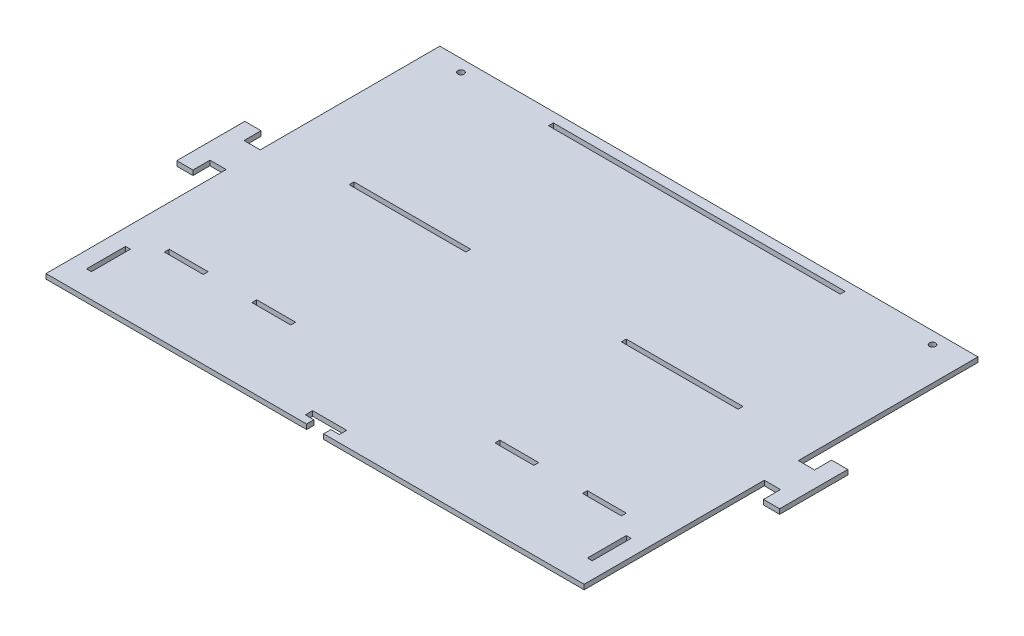
SolidWorks part; units mm, degrees
ref_plane "Alzado" through (0, 0, 0) normal (0, 0, 1) x (1, 0, 0)
ref_plane "Planta" through (0, 0, 0) normal (0, 1, 0) x (1, 0, 0)
ref_plane "Vista lateral" through (0, 0, 0) normal (1, 0, 0) x (0, 0, -1)
sketch "Croquis1" plane through (0, 0, 0) normal (0, 1, 0) x (1, 0, 0)
  line L4 (-447.0447, -95.6027) -> (-447.0447, -240.6027)
  line L5 (-2097.0447, -803.1027) -> (-437.0447, -803.1027)
  line L6 (-437.0447, 6.8973) -> (-437.0447, -803.1027)
  line L7 (-2097.0447, 6.8973) -> (-437.0447, 6.8973)
  line L13 (-2097.0447, 6.8973) -> (-2097.0447, -803.1027)
  line L18 (-2087.0447, -793.1027) -> (-447.0447, -793.1027) construction
  line L19 (-932.0447, -3.1027) -> (-632.0447, -3.1027)
  line L25 (-2097.0447, 6.8973) -> (-2097.0447, -803.1027) construction
  line L29 (-1117.0447, -3.1027) -> (-1417.0447, -3.1027)
  line L30 (-1117.0447, -8.1027) -> (-1117.0447, -3.1027)
  line L32 (-1417.0447, -3.1027) -> (-1417.0447, -8.1027)
  line L33 (-1602.0447, -8.1027) -> (-1902.0447, -8.1027)
  line L34 (-1902.0447, -3.1027) -> (-1602.0447, -3.1027)
  line L35 (-1902.0447, -3.1027) -> (-1902.0447, -8.1027)
  line L36 (-1602.0447, -3.1027) -> (-1602.0447, -8.1027)
  line L37 (-2097.0447, 6.8973) -> (-437.0447, 6.8973)
  line L38 (-632.0447, -3.1027) -> (-632.0447, -8.1027)
  line L39 (-2087.0447, -3.1027) -> (-447.0447, -3.1027) construction
  line L40 (-932.0447, -3.1027) -> (-932.0447, -8.1027)
  line L41 (-452.0447, -95.6027) -> (-452.0447, -90.6027)
  line L42 (-447.0447, -3.1027) -> (-447.0447, -793.1027) construction
  line L45 (-452.0447, -95.6027) -> (-452.0447, -240.6027)
  line L49 (-452.0447, -328.1027) -> (-452.0447, -473.1027)
  line L51 (-447.0447, -328.1027) -> (-447.0447, -473.1027)
  line L53 (-452.0447, -560.6027) -> (-452.0447, -705.6027)
  line L55 (-447.0447, -560.6027) -> (-447.0447, -705.6027)
  line L67 (-2087.0447, -3.1027) -> (-2087.0447, -793.1027) construction
  line L68 (-447.0447, -95.6027) -> (-447.0447, -90.6027)
  line L69 (-447.0447, -90.6027) -> (-452.0447, -90.6027)
  line L70 (-447.0447, -328.1027) -> (-447.0447, -323.1027)
  line L71 (-447.0447, -240.6027) -> (-452.0447, -240.6027) construction
  line L72 (-447.0447, -240.6027) -> (-452.0447, -240.6027)
  line L73 (-452.0447, -328.1027) -> (-452.0447, -323.1027)
  line L74 (-452.0447, -323.1027) -> (-447.0447, -323.1027)
  line L75 (-447.0447, -473.1027) -> (-452.0447, -473.1027)
  line L76 (-452.0447, -560.6027) -> (-452.0447, -555.6027)
  line L77 (-447.0447, -560.6027) -> (-447.0447, -555.6027)
  line L78 (-447.0447, -555.6027) -> (-452.0447, -555.6027)
  line L79 (-632.0447, -8.1027) -> (-932.0447, -8.1027)
  line L80 (-447.0447, -705.6027) -> (-452.0447, -705.6027)
  line L81 (-2087.0447, -240.6027) -> (-2082.0447, -240.6027) construction
  line L82 (-2087.0447, -705.6027) -> (-2082.0447, -705.6027)
  line L83 (-2087.0447, -555.6027) -> (-2082.0447, -555.6027)
  line L84 (-2087.0447, -560.6027) -> (-2087.0447, -555.6027)
  line L85 (-2082.0447, -560.6027) -> (-2082.0447, -555.6027)
  line L86 (-2087.0447, -473.1027) -> (-2082.0447, -473.1027)
  line L87 (-2082.0447, -323.1027) -> (-2087.0447, -323.1027)
  line L88 (-2082.0447, -328.1027) -> (-2082.0447, -323.1027)
  line L89 (-2087.0447, -240.6027) -> (-2082.0447, -240.6027)
  line L90 (-2087.0447, -328.1027) -> (-2087.0447, -323.1027)
  line L91 (-2087.0447, -90.6027) -> (-2082.0447, -90.6027)
  line L92 (-2087.0447, -95.6027) -> (-2087.0447, -90.6027)
  line L93 (-2087.0447, -560.6027) -> (-2087.0447, -705.6027)
  line L94 (-2082.0447, -560.6027) -> (-2082.0447, -705.6027)
  line L95 (-2087.0447, -328.1027) -> (-2087.0447, -473.1027)
  line L96 (-2082.0447, -328.1027) -> (-2082.0447, -473.1027)
  line L97 (-2082.0447, -95.6027) -> (-2082.0447, -240.6027)
  line L98 (-2082.0447, -95.6027) -> (-2082.0447, -90.6027)
  line L99 (-2087.0447, -95.6027) -> (-2087.0447, -240.6027)
  line L100 (-1117.0447, -8.1027) -> (-1417.0447, -8.1027)
  line L101 (-1117.0447, -788.1027) -> (-1417.0447, -788.1027)
  line L102 (-632.0447, -788.1027) -> (-932.0447, -788.1027)
  line L103 (-932.0447, -793.1027) -> (-932.0447, -788.1027)
  line L104 (-632.0447, -793.1027) -> (-632.0447, -788.1027)
  line L105 (-1602.0447, -793.1027) -> (-1602.0447, -788.1027)
  line L106 (-1902.0447, -793.1027) -> (-1902.0447, -788.1027)
  line L107 (-1902.0447, -793.1027) -> (-1602.0447, -793.1027)
  line L108 (-1602.0447, -788.1027) -> (-1902.0447, -788.1027)
  line L109 (-1417.0447, -793.1027) -> (-1417.0447, -788.1027)
  line L110 (-1117.0447, -788.1027) -> (-1117.0447, -793.1027)
  line L111 (-1117.0447, -793.1027) -> (-1417.0447, -793.1027)
  line L112 (-932.0447, -793.1027) -> (-632.0447, -793.1027)
  dimension "D5" = 5
  dimension "D10" = 145
  dimension "D3" = 1660
  dimension "D12" = 5
  dimension "D13" = 145
  dimension "D14" = 5
  dimension "D15" = 5
extrude "Saliente-Extruir3" add sketch "Croquis1" along normal blind 5 contours L7 L13 L5 L6 L112 L103 L102 L104 L108 L105 L107 L106 L99 L92 L91 L98 L97 L89 L34 L36 L33 L35 L4 L72 L45 L41 L69 L68 L51 L75 L49 L73 L74 L70 L38 L79 L40 L19 L55 L80 L53 L76 L78
sketch "Croquis2" plane through (0, 5, 0) normal (0, 1, 0) x (1, 0, 0)
  line L0 (-1007.0447, -463.1027) -> (-1007.0447, -423.1027)
  line L1 (-669.5447, -638.1027) -> (-699.5447, -638.1027)
  line L2 (-1067.0447, -638.1027) -> (-1187.0447, -638.1027)
  line L5 (-1467.0447, -633.1027) -> (-1347.0447, -633.1027)
  line L8 (-1602.0447, -788.1027) -> (-1902.0447, -788.1027) construction
  line L11 (-1672.0447, -788.1027) -> (-1667.0447, -788.1027)
  line L19 (-644.5447, -633.1027) -> (-644.5447, -638.1027)
  line L24 (-1464.5447, -483.1027) -> (-1344.5447, -483.1027)
  line L25 (-669.5447, -638.1027) -> (-669.5447, -633.1027)
  line L26 (-1672.0447, -8.1027) -> (-1667.0447, -8.1027)
  line L61 (-769.5447, -478.1027) -> (-802.0447, -478.1027)
  line L63 (-849.5447, -483.1027) -> (-817.0447, -483.1027)
  line L65 (-602.0447, -490.6027) -> (-602.0447, -535.6027)
  line L68 (-699.5447, -633.1027) -> (-669.5447, -633.1027)
  line L70 (-862.0447, -653.1027) -> (-862.0447, -698.1027)
  line L72 (-867.0447, -653.1027) -> (-867.0447, -698.1027)
  line L74 (-1032.0447, -313.1027) -> (-1072.0447, -313.1027)
  line L76 (-1162.0447, -318.1027) -> (-1122.0447, -318.1027)
  line L77 (-1012.0447, -333.1027) -> (-1012.0447, -373.1027)
  line L78 (-1064.5447, -478.1027) -> (-1184.5447, -478.1027)
  line L80 (-1122.0447, -313.1027) -> (-1122.0447, -318.1027)
  line L87 (-699.5447, -633.1027) -> (-699.5447, -638.1027)
  line L88 (-614.5447, -638.1027) -> (-644.5447, -638.1027)
  line L89 (-614.5447, -638.1027) -> (-614.5447, -633.1027)
  line L90 (-607.0447, -615.6027) -> (-602.0447, -615.6027)
  line L91 (-607.0447, -570.6027) -> (-602.0447, -570.6027)
  line L92 (-602.0447, -570.6027) -> (-602.0447, -615.6027)
  line L93 (-607.0447, -490.6027) -> (-607.0447, -535.6027)
  line L94 (-1187.0447, -158.1027) -> (-1187.0447, -163.1027)
  line L95 (-607.0447, -535.6027) -> (-602.0447, -535.6027)
  line L96 (-607.0447, -615.6027) -> (-607.0447, -570.6027)
  line L97 (-802.0447, -478.1027) -> (-802.0447, -483.1027)
  line L99 (-604.5447, -535.6027) -> (-602.0447, -535.6027) construction
  line L100 (-817.0447, -483.1027) -> (-817.0447, -478.1027)
  line L101 (-644.5447, -633.1027) -> (-614.5447, -633.1027)
  line L102 (-1467.0447, -158.1027) -> (-1467.0447, -163.1027)
  line L103 (-867.0447, -653.1027) -> (-862.0447, -653.1027)
  line L104 (-867.0447, -698.1027) -> (-862.0447, -698.1027)
  line L105 (-862.0447, -728.1027) -> (-867.0447, -728.1027)
  line L106 (-862.0447, -728.1027) -> (-862.0447, -773.1027)
  line L107 (-867.0447, -728.1027) -> (-867.0447, -773.1027)
  line L108 (-867.0447, -773.1027) -> (-862.0447, -773.1027)
  line L109 (-1347.0447, -638.1027) -> (-1467.0447, -638.1027)
  line L110 (-849.5447, -478.1027) -> (-849.5447, -483.1027)
  line L111 (-769.5447, -483.1027) -> (-769.5447, -478.1027)
  line L112 (-802.0447, -483.1027) -> (-769.5447, -483.1027)
  line L113 (-817.0447, -478.1027) -> (-849.5447, -478.1027)
  line L114 (-1267.0447, -8.1027) -> (-1267.0447, -98.1027)
  line L115 (-1064.5447, -478.1027) -> (-1064.5447, -483.1027)
  line L116 (-1184.5447, -478.1027) -> (-1184.5447, -483.1027)
  line L117 (-1464.5447, -478.1027) -> (-1464.5447, -483.1027)
  line L118 (-1344.5447, -478.1027) -> (-1344.5447, -483.1027)
  line L121 (-1184.5447, -483.1027) -> (-1064.5447, -483.1027)
  line L122 (-1344.5447, -478.1027) -> (-1464.5447, -478.1027)
  line L123 (-1117.0447, -8.1027) -> (-1417.0447, -8.1027) construction
  line L124 (-1412.0447, -313.1027) -> (-1412.0447, -318.1027) construction
  line L126 (-1067.0447, -633.1027) -> (-1067.0447, -638.1027)
  line L127 (-1187.0447, -638.1027) -> (-1187.0447, -633.1027)
  line L128 (-1347.0447, -638.1027) -> (-1347.0447, -633.1027)
  line L129 (-1467.0447, -633.1027) -> (-1467.0447, -638.1027)
  line L130 (-1187.0447, -633.1027) -> (-1067.0447, -633.1027)
  line L131 (-1412.0447, -313.1027) -> (-1372.0447, -313.1027)
  line L132 (-1927.0447, -305.6027) -> (-1932.0447, -305.6027)
  line L133 (-1462.0447, -318.1027) -> (-1502.0447, -318.1027)
  line L134 (-1012.0447, -423.1027) -> (-1012.0447, -463.1027)
  line L136 (-1012.0447, -463.1027) -> (-1007.0447, -463.1027)
  line L137 (-1012.0447, -423.1027) -> (-1007.0447, -423.1027)
  line L138 (-1012.0447, -373.1027) -> (-1007.0447, -373.1027)
  line L139 (-1007.0447, -333.1027) -> (-1012.0447, -333.1027)
  line L140 (-1007.0447, -373.1027) -> (-1007.0447, -333.1027)
  line L141 (-1032.0447, -313.1027) -> (-1032.0447, -318.1027)
  line L142 (-1072.0447, -313.1027) -> (-1072.0447, -318.1027)
  line L143 (-1372.0447, -313.1027) -> (-1372.0447, -318.1027)
  line L144 (-1162.0447, -313.1027) -> (-1162.0447, -318.1027)
  line L145 (-1122.0447, -313.1027) -> (-1122.0447, -318.1027) construction
  line L146 (-1072.0447, -318.1027) -> (-1032.0447, -318.1027)
  line L147 (-1122.0447, -313.1027) -> (-1162.0447, -313.1027)
  line L148 (-1929.5447, -535.6027) -> (-1932.0447, -535.6027) construction
  line L149 (-1717.0447, -478.1027) -> (-1684.5447, -478.1027)
  line L150 (-1732.0447, -483.1027) -> (-1764.5447, -483.1027)
  line L151 (-1764.5447, -483.1027) -> (-1764.5447, -478.1027)
  line L152 (-1684.5447, -478.1027) -> (-1684.5447, -483.1027)
  line L153 (-1717.0447, -483.1027) -> (-1717.0447, -478.1027)
  line L154 (-1732.0447, -478.1027) -> (-1732.0447, -483.1027)
  line L155 (-1927.0447, -535.6027) -> (-1932.0447, -535.6027)
  line L156 (-1462.0447, -313.1027) -> (-1462.0447, -318.1027)
  line L157 (-1927.0447, -490.6027) -> (-1927.0447, -535.6027)
  line L159 (-1932.0447, -490.6027) -> (-1932.0447, -535.6027)
  line L160 (-1684.5447, -483.1027) -> (-1717.0447, -483.1027)
  line L161 (-1764.5447, -478.1027) -> (-1732.0447, -478.1027)
  line L162 (-1667.0447, -773.1027) -> (-1672.0447, -773.1027)
  line L163 (-1467.0447, -158.1027) -> (-1347.0447, -158.1027)
  line L164 (-1067.0447, -163.1027) -> (-1187.0447, -163.1027)
  line L165 (-1502.0447, -313.1027) -> (-1502.0447, -318.1027)
  line L166 (-1527.0447, -373.1027) -> (-1527.0447, -333.1027)
  line L167 (-1527.0447, -333.1027) -> (-1522.0447, -333.1027)
  line L168 (-1522.0447, -373.1027) -> (-1527.0447, -373.1027)
  line L169 (-1522.0447, -423.1027) -> (-1527.0447, -423.1027)
  line L170 (-1522.0447, -423.1027) -> (-1522.0447, -463.1027)
  line L171 (-1667.0447, -728.1027) -> (-1667.0447, -773.1027)
  line L172 (-1672.0447, -728.1027) -> (-1672.0447, -773.1027)
  line L173 (-1672.0447, -728.1027) -> (-1667.0447, -728.1027)
  line L174 (-1667.0447, -698.1027) -> (-1672.0447, -698.1027)
  line L175 (-1667.0447, -653.1027) -> (-1672.0447, -653.1027)
  line L176 (-1889.5447, -633.1027) -> (-1919.5447, -633.1027)
  line L177 (-1927.0447, -615.6027) -> (-1927.0447, -570.6027)
  line L178 (-1932.0447, -570.6027) -> (-1932.0447, -615.6027)
  line L179 (-1927.0447, -570.6027) -> (-1932.0447, -570.6027)
  line L180 (-1927.0447, -615.6027) -> (-1932.0447, -615.6027)
  line L181 (-1919.5447, -638.1027) -> (-1919.5447, -633.1027)
  line L182 (-1919.5447, -638.1027) -> (-1889.5447, -638.1027)
  line L183 (-1834.5447, -633.1027) -> (-1834.5447, -638.1027)
  line L184 (-1667.0447, -653.1027) -> (-1667.0447, -698.1027)
  line L185 (-1672.0447, -653.1027) -> (-1672.0447, -698.1027)
  line L186 (-1834.5447, -633.1027) -> (-1864.5447, -633.1027)
  line L187 (-1864.5447, -638.1027) -> (-1864.5447, -633.1027)
  line L188 (-1889.5447, -633.1027) -> (-1889.5447, -638.1027)
  line L189 (-1412.0447, -313.1027) -> (-1412.0447, -318.1027)
  line L190 (-1522.0447, -333.1027) -> (-1522.0447, -373.1027)
  line L191 (-1864.5447, -638.1027) -> (-1834.5447, -638.1027)
  line L192 (-1187.0447, -158.1027) -> (-1067.0447, -158.1027)
  line L193 (-1372.0447, -318.1027) -> (-1412.0447, -318.1027)
  line L194 (-1347.0447, -158.1027) -> (-1347.0447, -163.1027)
  line L195 (-1502.0447, -313.1027) -> (-1462.0447, -313.1027)
  line L196 (-1067.0447, -163.1027) -> (-1067.0447, -158.1027)
  line L197 (-1347.0447, -163.1027) -> (-1467.0447, -163.1027)
  line L198 (-1527.0447, -463.1027) -> (-1527.0447, -423.1027)
  line L199 (-1522.0447, -463.1027) -> (-1527.0447, -463.1027)
  line L200 (-1927.0447, -490.6027) -> (-1932.0447, -490.6027)
  line L201 (-602.0447, -490.6027) -> (-607.0447, -490.6027)
  line L202 (-602.0447, -305.6027) -> (-607.0447, -305.6027)
  line L206 (-604.5447, -260.6027) -> (-602.0447, -260.6027) construction
  line L207 (-817.0447, -318.1027) -> (-849.5447, -318.1027)
  line L208 (-802.0447, -313.1027) -> (-769.5447, -313.1027)
  line L209 (-769.5447, -313.1027) -> (-769.5447, -318.1027)
  line L210 (-849.5447, -318.1027) -> (-849.5447, -313.1027)
  line L211 (-867.0447, -23.1027) -> (-862.0447, -23.1027)
  line L212 (-867.0447, -68.1027) -> (-867.0447, -23.1027)
  line L213 (-862.0447, -68.1027) -> (-862.0447, -23.1027)
  line L214 (-862.0447, -68.1027) -> (-867.0447, -68.1027)
  line L215 (-867.0447, -98.1027) -> (-862.0447, -98.1027)
  line L216 (-867.0447, -143.1027) -> (-862.0447, -143.1027)
  line L217 (-644.5447, -163.1027) -> (-614.5447, -163.1027)
  line L218 (-817.0447, -313.1027) -> (-817.0447, -318.1027)
  line L219 (-802.0447, -318.1027) -> (-802.0447, -313.1027)
  line L220 (-607.0447, -180.6027) -> (-607.0447, -225.6027)
  line L221 (-607.0447, -260.6027) -> (-602.0447, -260.6027)
  line L223 (-607.0447, -305.6027) -> (-607.0447, -260.6027)
  line L224 (-602.0447, -225.6027) -> (-602.0447, -180.6027)
  line L225 (-607.0447, -225.6027) -> (-602.0447, -225.6027)
  line L226 (-607.0447, -180.6027) -> (-602.0447, -180.6027)
  line L227 (-614.5447, -158.1027) -> (-614.5447, -163.1027)
  line L228 (-614.5447, -158.1027) -> (-644.5447, -158.1027)
  line L229 (-699.5447, -163.1027) -> (-699.5447, -158.1027)
  line L230 (-867.0447, -143.1027) -> (-867.0447, -98.1027)
  line L231 (-862.0447, -143.1027) -> (-862.0447, -98.1027)
  line L232 (-699.5447, -163.1027) -> (-669.5447, -163.1027)
  line L234 (-602.0447, -305.6027) -> (-602.0447, -260.6027)
  line L235 (-849.5447, -313.1027) -> (-817.0447, -313.1027)
  line L236 (-769.5447, -318.1027) -> (-802.0447, -318.1027)
  line L237 (-669.5447, -158.1027) -> (-669.5447, -163.1027)
  line L238 (-644.5447, -163.1027) -> (-644.5447, -158.1027)
  line L239 (-669.5447, -158.1027) -> (-699.5447, -158.1027)
  line L240 (-1929.5447, -260.6027) -> (-1932.0447, -260.6027) construction
  line L241 (-1864.5447, -158.1027) -> (-1834.5447, -158.1027)
  line L242 (-1889.5447, -163.1027) -> (-1889.5447, -158.1027)
  line L243 (-1864.5447, -158.1027) -> (-1864.5447, -163.1027)
  line L244 (-1834.5447, -163.1027) -> (-1864.5447, -163.1027)
  line L245 (-1672.0447, -143.1027) -> (-1672.0447, -98.1027)
  line L246 (-1667.0447, -143.1027) -> (-1667.0447, -98.1027)
  line L247 (-1834.5447, -163.1027) -> (-1834.5447, -158.1027)
  line L248 (-1919.5447, -158.1027) -> (-1889.5447, -158.1027)
  line L249 (-1919.5447, -158.1027) -> (-1919.5447, -163.1027)
  line L250 (-1927.0447, -180.6027) -> (-1932.0447, -180.6027)
  line L251 (-1927.0447, -225.6027) -> (-1932.0447, -225.6027)
  line L252 (-1932.0447, -225.6027) -> (-1932.0447, -180.6027)
  line L253 (-1927.0447, -180.6027) -> (-1927.0447, -225.6027)
  line L254 (-1889.5447, -163.1027) -> (-1919.5447, -163.1027)
  line L255 (-1667.0447, -143.1027) -> (-1672.0447, -143.1027)
  line L256 (-1667.0447, -98.1027) -> (-1672.0447, -98.1027)
  line L257 (-1672.0447, -68.1027) -> (-1667.0447, -68.1027)
  line L258 (-1672.0447, -68.1027) -> (-1672.0447, -23.1027)
  line L259 (-1667.0447, -68.1027) -> (-1667.0447, -23.1027)
  line L260 (-1667.0447, -23.1027) -> (-1672.0447, -23.1027)
  line L261 (-1764.5447, -318.1027) -> (-1732.0447, -318.1027)
  line L262 (-1684.5447, -313.1027) -> (-1717.0447, -313.1027)
  line L263 (-1932.0447, -305.6027) -> (-1932.0447, -260.6027)
  line L265 (-1927.0447, -305.6027) -> (-1927.0447, -260.6027)
  line L267 (-1927.0447, -260.6027) -> (-1932.0447, -260.6027)
  line L268 (-1732.0447, -318.1027) -> (-1732.0447, -313.1027)
  line L269 (-1717.0447, -313.1027) -> (-1717.0447, -318.1027)
  line L270 (-1684.5447, -318.1027) -> (-1684.5447, -313.1027)
  line L271 (-1764.5447, -313.1027) -> (-1764.5447, -318.1027)
  line L272 (-1732.0447, -313.1027) -> (-1764.5447, -313.1027)
  line L273 (-1717.0447, -318.1027) -> (-1684.5447, -318.1027)
  dimension "D1" = 120
extrude "Cortar-Extruir2" cut sketch "Croquis2" against normal blind 10 contours L226 L220 L225 L224 | L238 L217 L227 L228 | L214 L213 L211 L212 | L216 L231 L215 L230 | L236 L209 L208 L219 | L235 L210 L207 L218 | L93 L95 L65 L202 | L96 L90 L92 L91 | L97 L112 L111 L61 | L100 L113 L110 L63 | L107 L108 L106 L105 | L175 L185 L174 L184 | L173 L172 L162 L171 | L187 L191 L183 L186 | L259 L260 L258 L257 | L246 L256 L245 L255 | L232 L237 L239 L229 | L101 L89 L88 L19 | L68 L25 L1 L87 | L70 L104 L72 L103 | L134 L136 L0 L137 | L78 L116 L121 L115 | L77 L138 L140 L139 | L74 L142 L146 L141 | L76 L80 L147 L144 | L164 L94 L192 L196 | L130 L126 L2 L127 | L24 L118 L122 L117 | L163 L194 L197 L102 | L5 L128 L109 L129 | L176 L181 L182 L188 | L177 L179 L178 L180 | L159 L155 L157 L200 | L263 L267 L265 L132 | L252 L250 L253 L251 | L248 L242 L254 L249 | L241 L247 L244 L243 | L262 L269 L273 L270 | L149 L152 L160 L153 | L150 L151 L161 L154 | L261 L268 L272 L271 | L166 L167 L190 L168 | L169 L198 L199 L170 | L133 L165 L195 L156 | L131 L143 L193 L189
sketch "Croquis3" plane through (0, 5, 0) normal (0, 1, 0) x (1, 0, 0)
  line L0 (-2084.5447, -240.6027) -> (-2084.5447, -323.1027) construction
  line L1 (-2087.0447, -240.6027) -> (-2082.0447, -240.6027) construction
  line L2 (-2082.0447, -323.1027) -> (-2087.0447, -323.1027) construction
  line L3 (-2084.5447, -473.1027) -> (-2084.5447, -555.6027) construction
  line L4 (-2087.0447, -473.1027) -> (-2082.0447, -473.1027) construction
  line L5 (-2087.0447, -555.6027) -> (-2082.0447, -555.6027) construction
  line L6 (-1602.0447, -790.6027) -> (-1417.0447, -790.6027) construction
  line L7 (-1602.0447, -793.1027) -> (-1602.0447, -788.1027) construction
  line L8 (-1417.0447, -793.1027) -> (-1417.0447, -788.1027) construction
  line L9 (-932.0447, -790.6027) -> (-1117.0447, -790.6027) construction
  line L10 (-932.0447, -793.1027) -> (-932.0447, -788.1027) construction
  line L11 (-1117.0447, -788.1027) -> (-1117.0447, -793.1027) construction
  line L12 (-449.5447, -473.1027) -> (-449.5447, -555.6027) construction
  line L13 (-447.0447, -473.1027) -> (-452.0447, -473.1027) construction
  line L14 (-447.0447, -555.6027) -> (-452.0447, -555.6027) construction
  line L15 (-449.5447, -240.6027) -> (-449.5447, -323.1027) construction
  line L16 (-447.0447, -240.6027) -> (-452.0447, -240.6027) construction
  line L17 (-452.0447, -323.1027) -> (-447.0447, -323.1027) construction
  line L18 (-1117.0447, -8.1027) -> (-1117.0447, -3.1027) construction
  line L19 (-932.0447, -5.6027) -> (-1117.0447, -5.6027) construction
  line L20 (-932.0447, -3.1027) -> (-932.0447, -8.1027) construction
  line L21 (-1417.0447, -5.6027) -> (-1602.0447, -5.6027) construction
  line L22 (-1417.0447, -3.1027) -> (-1417.0447, -8.1027) construction
  line L23 (-1602.0447, -3.1027) -> (-1602.0447, -8.1027) construction
  circle A0 centre (-2084.5447, -281.8527) radius 3.2
  circle A1 centre (-2084.5447, -514.3527) radius 3.2
  circle A2 centre (-1509.5447, -790.6027) radius 3.2
  circle A3 centre (-1024.5447, -790.6027) radius 3.2
  circle A4 centre (-449.5447, -514.3527) radius 3.2
  circle A5 centre (-449.5447, -281.8527) radius 3.2
  circle A6 centre (-1024.5447, -5.6027) radius 3.2
  circle A7 centre (-1509.5447, -5.6027) radius 3.2
extrude "Cortar-Extruir3" cut sketch "Croquis3" against normal blind 10
sketch "Croquis5" plane through (0, 5, 0) normal (0, 1, 0) x (1, 0, 0)
  line L0 (-437.0447, -398.1027) -> (-2097.0447, -398.1027) construction
  line L1 (-437.0447, 6.8973) -> (-437.0447, -803.1027) construction
  line L2 (-2097.0447, 6.8973) -> (-2097.0447, -803.1027) construction
  line L3 (-437.0447, -398.1027) -> (-990.3447, -398.1027) construction
  line L4 (-990.3447, -160.342) -> (-990.3447, -177.842) construction
  line L5 (-990.3447, -177.842) -> (-973.6947, -177.842) construction
  line L6 (-1267.0447, -398.1027) -> (-437.0447, -398.1027) construction
  line L7 (-437.0447, -398.1027) -> (-852.0447, -398.1027) construction
  line L8 (-990.3447, 6.8973) -> (-990.3447, -803.1027) construction
  line L9 (-2097.0447, 6.8973) -> (-437.0447, 6.8973) construction
  line L10 (-2097.0447, -803.1027) -> (-437.0447, -803.1027) construction
  line L11 (-1267.0447, -411.2781) -> (-1267.0447, -266.4251) construction
  line L12 (-1543.7447, 6.8973) -> (-1543.7447, -803.1027) construction
  line L13 (-990.3447, -398.1027) -> (-990.3447, -195.342) construction
  line L14 (-990.3447, -195.342) -> (-957.0447, -195.342) construction
  line L15 (-957.0447, -195.342) -> (-957.0447, -230.342) construction
  line L16 (-957.0447, -230.342) -> (-990.3447, -230.342) construction
  line L17 (-957.0447, -195.342) -> (-957.0447, -160.342) construction
  line L18 (-957.0447, -160.342) -> (-990.3447, -160.342) construction
  line L19 (-973.6947, -177.842) -> (-973.6947, -160.342) construction
  line L20 (-990.3447, -212.842) -> (-973.6947, -212.842) construction
  line L21 (-973.6947, -212.842) -> (-973.6947, -230.342) construction
  line L22 (-990.3447, -212.842) -> (-973.6947, -212.842)
  line L23 (-973.6947, -212.842) -> (-973.6947, -230.342)
  line L24 (-973.6947, -230.342) -> (-957.0447, -230.342)
  line L25 (-957.0447, -230.342) -> (-957.0447, -160.342)
  line L26 (-957.0447, -160.342) -> (-973.6947, -160.342)
  line L27 (-973.6947, -160.342) -> (-973.6947, -177.842)
  line L28 (-973.6947, -177.842) -> (-990.3447, -177.842)
  line L29 (-990.3447, -177.842) -> (-990.3447, -212.842)
  line L30 (-1560.3947, -177.842) -> (-1543.7447, -177.842)
  line L31 (-1560.3947, -160.342) -> (-1560.3947, -177.842)
  line L32 (-1577.0447, -160.342) -> (-1560.3947, -160.342)
  line L33 (-1577.0447, -230.342) -> (-1577.0447, -160.342)
  line L34 (-1560.3947, -230.342) -> (-1577.0447, -230.342)
  line L35 (-1560.3947, -212.842) -> (-1560.3947, -230.342)
  line L36 (-1543.7447, -212.842) -> (-1560.3947, -212.842)
  line L37 (-1543.7447, -177.842) -> (-1543.7447, -212.842)
  line L38 (-1267.0447, -398.1027) -> (-1267.0447, -383.1027) construction
  line L39 (-1267.0447, -398.1027) -> (-1249.5447, -398.1027) construction
  line L40 (-1249.5447, -398.1027) -> (-1249.5447, -383.1027) construction
  line L41 (-1249.5447, -383.1027) -> (-1267.0447, -383.1027) construction
  line L42 (-1267.0447, -383.1027) -> (-1284.5447, -383.1027) construction
  line L43 (-1284.5447, -383.1027) -> (-1284.5447, -398.1027) construction
  line L44 (-1284.5447, -398.1027) -> (-1267.0447, -398.1027) construction
  line L45 (-1249.5447, -398.1027) -> (-1258.2947, -398.1027) construction
  line L46 (-1275.7947, -390.6027) -> (-1275.7947, -398.1027) construction
  line L47 (-1249.5447, -390.6027) -> (-1258.2947, -390.6027) construction
  line L48 (-1258.2947, -390.6027) -> (-1258.2947, -398.1027) construction
  line L49 (-1284.5447, -390.6027) -> (-1275.7947, -390.6027) construction
  line L51 (-1275.7947, -398.1027) -> (-1275.7947, -390.6027)
  line L52 (-1275.7947, -390.6027) -> (-1284.5447, -390.6027)
  line L53 (-1284.5447, -390.6027) -> (-1284.5447, -383.1027)
  line L54 (-1284.5447, -383.1027) -> (-1249.5447, -383.1027)
  line L55 (-1249.5447, -383.1027) -> (-1249.5447, -390.6027)
  line L56 (-1249.5447, -390.6027) -> (-1258.2947, -390.6027)
  line L57 (-1258.2947, -398.1027) -> (-1258.2947, -390.6027)
  line L58 (-990.3447, 6.8973) -> (-990.3447, -160.342)
  line L59 (-973.6947, -177.842) -> (-973.6947, -160.342)
  line L60 (-990.3447, -230.342) -> (-990.3447, -398.1027)
  line L61 (-990.3447, -398.1027) -> (-1258.2947, -398.1027)
  line L62 (-1543.7447, -398.1027) -> (-1275.7947, -398.1027)
  line L63 (-1543.7447, -398.1027) -> (-1543.7447, -230.342)
  line L64 (-1543.7447, -230.342) -> (-1543.7447, -212.842)
  line L66 (-1543.7447, -160.342) -> (-1543.7447, 6.8973)
  line L67 (-1543.7447, 6.8973) -> (-2097.0447, 6.8973)
  line L68 (-2097.0447, 6.8973) -> (-2097.0447, -803.1027)
  line L69 (-2097.0447, -803.1027) -> (-437.0447, -803.1027)
  line L70 (-437.0447, -803.1027) -> (-437.0447, 6.8973)
  line L71 (-437.0447, 6.8973) -> (-990.3447, 6.8973)
  line L72 (-990.3447, -230.342) -> (-990.3447, -212.842)
  line L73 (-990.3447, -177.842) -> (-990.3447, -160.342)
  line L79 (-1543.7447, -177.842) -> (-1543.7447, -160.342)
  dimension "D1" = 33.3
extrude "Cortar-Extruir5" cut sketch "Croquis5" against normal blind 10 contours L30 L79 L66 L67 L68 L69 L70 L71 L58 L73 L28 L27 L26 L25 L24 L23 L22 L72 L60 L61 L57 L56 L55 L54 L53 L52 L51 L62 L63 L64 L36 L35 L34 L33 L32 L31
